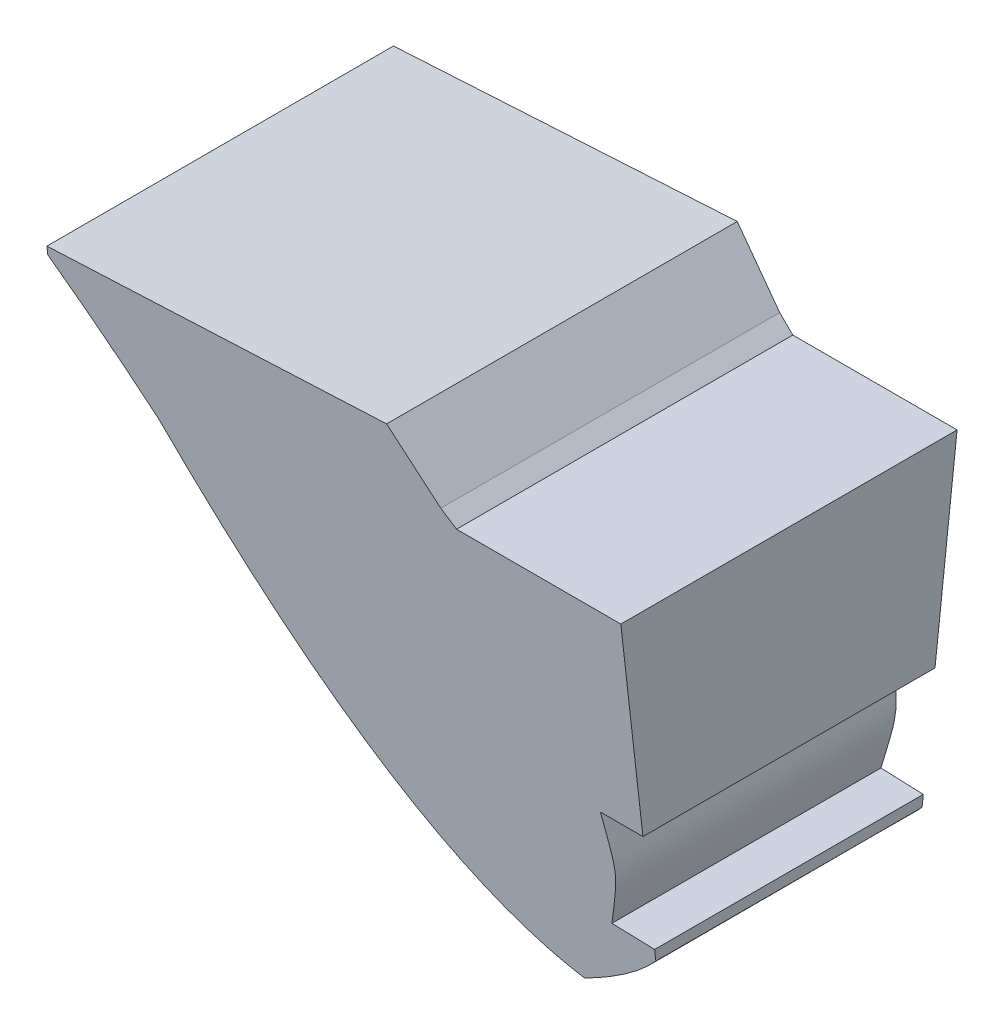
SolidWorks part; units mm, degrees
ref_plane "Alzado" through (0, 0, 0) normal (0, 0, 1) x (1, 0, 0)
ref_plane "Planta" through (0, 0, 0) normal (0, 1, 0) x (1, 0, 0)
ref_plane "Vista lateral" through (0, 0, 0) normal (1, 0, 0) x (0, 0, -1)
sketch "Croquis1" plane through (0, 0, 0) normal (0, 0, 1) x (1, 0, 0)
  line L0 (-8.9818, 12.6082) -> (-23.0359, 11.8716) construction
  line L1 (-8.9818, 12.6082) -> (-23.0359, 11.8716)
  line L2 (-8.9818, 12.6082) -> (-23.0359, 11.8716) construction
  line L4 (-8.9818, 12.6082) -> (-23.0359, 11.8716)
  line L6 (-1.3949, 1.9763) -> (0.3551, 2.2848) construction
  line L7 (-1.3949, 1.9763) -> (0.3551, 2.2848)
  line L8 (0.3551, 2.2848) -> (0.3551, 2.8423) construction
  line L9 (0.3551, 2.2848) -> (0.3551, 3.0015)
  line L10 (0.3551, -2.2848) -> (-1.3949, -2.2237) construction
  line L11 (0.3551, -2.2848) -> (-1.3949, -2.2237)
  line L12 (0.3551, 2.2848) -> (0.3551, -2.2848) construction
  line L13 (0.3551, -2.2848) -> (0.3551, -2.7233)
  line L14 (-8.9818, 12.6082) -> (-6.9949, 10.4774)
  line L15 (-23.0359, 11.5401) -> (-23.0359, 11.8716) construction
  line L16 (-23.0359, 11.5401) -> (-23.0359, 11.8716)
  arc A0 (-18.9452, 7.5409) -> (-23.0359, 11.5401) centre (-69.8841, -40.4718) ccw construction
  arc A1 (-18.9452, 7.5409) -> (-23.0359, 11.5401) centre (-69.8841, -40.4718) ccw
  spline S1 degree 2 poles (-828.7061, 3922.2202) (545.889, -3962.7836) (-262.0834, 3982.5902) knots 0.462185 0.462185 0.462185 0.537731 0.537731 0.537731 weights 1 1 1 only from (-18.9452, 7.5409) to (-2.8466, -5.0591) construction
  spline S2 degree 2 poles (-18.9452, 7.5409) (-10.215, -3.6976) (-2.8466, -5.0591) knots 0.497667 0.497667 0.497667 0.499554 0.499554 0.499554 weights 1 1 1
  spline S3 degree 2 poles (-3804.8689, 1232.5771) (3762.9122, -1369.6643) (-3716.5752, 1504.852) knots 0.462212 0.462212 0.462212 0.537836 0.537836 0.537836 weights 1 1 1 only from (0.3551, 3.0015) to (-6.9949, 10.4774) construction
  spline S4 degree 2 poles (0.3551, 3.0015) (-1.4487, 6.0584) (-6.9949, 10.4774) knots 0.500821 0.500821 0.500821 0.502013 0.502013 0.502013 weights 1 1 1
  spline S5 degree 2 poles (-1.3949, -2.2237) (-0.9075, -0.1237) (-1.3949, 1.9763) knots 0 0 0 1 1 1 weights 1 3.231801 1 construction
  spline S6 degree 2 poles (-1.3949, -2.2237) (-0.9075, -0.1237) (-1.3949, 1.9763) knots 0 0 0 1 1 1 weights 1 3.231801 1
  spline S7 degree 2 poles (-3997.263, 185.0077) (3984.2333, -348.7483) (-3965.0625, 511.2595) knots 0.462205 0.462205 0.462205 0.537778 0.537778 0.537778 weights 1 1 1 only from (-2.8466, -5.0591) to (0.3551, -2.7233) construction
  spline S8 degree 2 poles (-2.8466, -5.0591) (-0.7424, -3.9352) (0.3551, -2.7233) knots 0.498812 0.498812 0.498812 0.499413 0.499413 0.499413 weights 1 1 1
extrude "Saliente-Extruir1" add sketch "Croquis1" along normal mid plane 14.42 contours S2 S8 L13 L11 S6 L7 L9 S4 L14 L1 L16 A1
sketch "Croquis3" plane through (0, 0, 0) normal (0, 0, 1) x (1, 0, 0)
  line L0 (-6.742, 0) -> (0, 0) construction
  line L1 (-1.8181, 2) -> (-1.7771, 2.0103) construction
  line L3 (-1.8181, 2) -> (-0.1689, 2.4155) construction
  line L4 (-1.8181, 2) -> (0.3551, 3.0015)
  line L5 (0.3551, 3.0015) -> (0.3551, 0)
  line L6 (-1.9112, -2.1782) -> (0.3551, -2.2848)
  line L7 (0.3551, -2.2848) -> (0.3551, 0)
  parabola Q0 (-1.9112, -2.1782) -> (-1.8181, 2) focus (-3.3181, 0) apex (-1.3181, 0)
  dimension "D1" = 2
  dimension "D2" = 2
extrude "Cortar-Extruir1" [suppressed] cut sketch "Croquis3" against normal through all both and the other way through all
sketch "Croquis4" plane through (0, 0, 0) normal (0, 0, 1) x (1, 0, 0)
  line L0 (-1.3949, 1.9763) -> (0.3551, 2.2848) construction
  line L1 (-1.3949, 1.9763) -> (0.3551, 2.2848)
  line L2 (0.3551, 2.2848) -> (0.3551, 3.0015) construction
  line L3 (0.3551, 1.9763) -> (0.3551, 2.2848)
  line L4 (-1.3949, 1.9763) -> (0.3551, 1.9763)
  line L5 (0, 0) -> (-3.4665, 0) construction
  dimension "D1" = 0
extrude "Saliente-Extruir2" add sketch "Croquis4" along normal through all and the other way through all
sketch "Croquis7" plane through (0, 0, 0) normal (0, 0, 1) x (1, 0, 0)
  line L0 (0, 0) -> (-15.3945, 3.3171) construction
  line L1 (-17.3963, 18.9371) -> (-15.3945, 3.3171) construction
  line L2 (-15.3945, 3.3171) -> (-9.9316, -2.6296) construction
  line L3 (-15.3945, 3.3171) -> (-10.2385, 8.0535) construction
  line L4 (-17.3963, 18.9371) -> (-16.5429, 12.2783) construction
  line L5 (0, 0) -> (-1.3461, -2.2254) construction
  line L6 (-69.8841, 29.5282) -> (-81.9382, 42.5765) construction
  line L7 (-69.8841, 29.5282) -> (-20.9497, 29.5282) construction
  line L8 (-17.8101, 13.1658) -> (-25.5429, 13.1658)
  line L9 (-18.2059, 7.0951) -> (-21.9246, 11.9299) construction
  line L10 (0.3551, -2.5) -> (-2.4497, -2.0473)
  line L11 (-1.3461, -2.2254) -> (-2.0075, -3.6222) construction
  line L12 (-1.3461, -2.2254) -> (-1.4547, -2.8987) construction
  line L13 (-1.3461, -2.2254) -> (-1.2286, -1.4976) construction
  line L14 (0.3551, -2.2848) -> (0.3551, -2.7233) construction
  line L15 (0.3551, -2.2848) -> (-1.3949, -2.2237) construction
  line L16 (-2.0075, -3.6222) -> (-3.0629, -5.8512) construction
  line L17 (-2.6331, -4.9434) -> (-3.7044, -5.5324) construction
  line L18 (-2.6331, -4.9434) -> (-3.2248, -3.867) construction
  line L19 (-2.6331, -4.9434) -> (-2.2174, -6.1341) construction
  line L20 (-4.0838, -4.7637) -> (-1.6363, -5.0668) construction
  line L21 (-4.0838, -4.7637) -> (-0.036, -5.9454) construction
  line L22 (-4.0838, -4.7637) -> (-3.7621, -3.6616) construction
  line L23 (-4.0838, -4.7637) -> (-6.31, -3.7023) construction
  line L24 (-6.31, -3.7023) -> (-8.69, -2.5677) construction
  line L25 (-8.69, -2.5677) -> (-6.8421, -3.7725) construction
  line L26 (-8.69, -2.5677) -> (-7.9481, -1.4297) construction
  line L27 (-10.6884, -0.8477) -> (-8.69, -2.5677) construction
  line L28 (-10.6884, -0.8477) -> (-14.8546, 2.738) construction
  line L29 (-14.8546, 2.738) -> (-14.5337, 2.3989) construction
  line L30 (-14.8546, 2.738) -> (-14.6199, 2.9602) construction
  line L31 (-18.2059, 7.0951) -> (-14.8546, 2.738) construction
  line L32 (-8.9818, 12.6082) -> (-23.0359, 11.8716) construction
  line L33 (-8.9818, 12.6082) -> (-23.0359, 11.8716)
  line L34 (-21.9246, 11.9299) -> (-21.9826, 13.0367) construction
  line L35 (-21.9246, 11.9299) -> (-23.4156, 13.0367) construction
  arc A0 (-18.9452, 7.5409) -> (-23.0359, 11.5401) centre (-69.8841, -40.4718) ccw construction
  spline S0 degree 2 poles (-473.2528, 1954.0983) (272.8543, -1983.3606) (-71.9703, 1991.8157) knots 0.473236 0.473236 0.473236 0.526647 0.526647 0.526647 weights 1 1 1 only from (-18.9452, 7.5409) to (-2.8466, -5.0591) construction
  spline S1 degree 2 poles (-18.6263, 7.1332) (-10.0803, -3.7225) (-2.8466, -5.0591) knots 0.497702 0.497702 0.497702 0.499554 0.499554 0.499554 weights 1 1 1 construction
  spline S3 degree 2 poles (-2001.337, 58.5738) (1992.5148, -174.5103) (-1977.5574, 289.1588) knots 0.473271 0.473271 0.473271 0.526705 0.526705 0.526705 weights 1 1 1 only from (-2.8466, -5.0591) to (0.3551, -2.7233) construction
  spline S4 degree 2 poles (-2.8466, -5.0591) (-2.7385, -5.0013) (-2.6331, -4.9434) knots 0.498812 0.498812 0.498812 0.498843 0.498843 0.498843 weights 1 1 1
  dimension "D1" = 2.5
  dimension "D2" = 22
  dimension "D3" = 16.17
  dimension "D4" = 54.138
  dimension "D5" = 34.566
  dimension "D6" = 50.413
sketch "Croquis6" plane through (0, 0, 0) normal (1, 0, 0) x (0, 0, -1)
  line L0 (7.21, 12.6082) -> (7.21, 10.4774) construction
  line L1 (7.21, 12.6082) -> (7.21, -5.0591)
  line L2 (-7.21, 12.6082) -> (-7.21, 10.4774) construction
  line L3 (-7.21, 12.6082) -> (-7.21, -5.0591)
  line L4 (-7.21, -5.0591) -> (7.21, -5.0591) construction
  line L5 (-7.21, -5.0591) -> (-5.21, -5.0591)
  line L6 (7.21, 12.6082) -> (5.21, -5.0591)
  line L7 (-7.21, 12.6082) -> (-5.21, -5.0591)
  line L8 (5.21, -5.0591) -> (7.21, -5.0591)
  dimension "D1" = 2
  dimension "D2" = 2
extrude "Cortar-Extruir2" cut sketch "Croquis6" against normal through all and the other way through all
sketch "Croquis8" plane through (0, 0, 0) normal (0, 0, 1) x (1, 0, 0)
  line L1 (-6.4017, 10) -> (0.3551, 10)
  line L2 (0.3551, 1.9763) -> (0.3551, 3.0015) construction
  line L3 (0.3551, 3.0015) -> (0.3551, 10)
  spline S0 degree 2 poles (-2783.6038, 1144.9234) (2823.3692, -1027.6829) (-2858.7361, 908.5992) knots 0.470055 0.470055 0.470055 0.535557 0.535557 0.535557 weights 1 1 1 only from (-6.9949, 10.4774) to (0.3551, 3.0015) construction
  spline S1 degree 2 poles (-6.4017, 10) (-1.3505, 5.8919) (0.3551, 3.0015) knots 0.500886 0.500886 0.500886 0.502013 0.502013 0.502013 weights 1 1 1
  dimension "D1" = 10
  dimension "D2" = 90
extrude "Saliente-Extruir3" add sketch "Croquis8" along normal up to surface and the other way up to surface up to face at (-6.8548, 3.8413, 6.2176) other way up to face at (-6.9269, 3.652, -6.1961)
